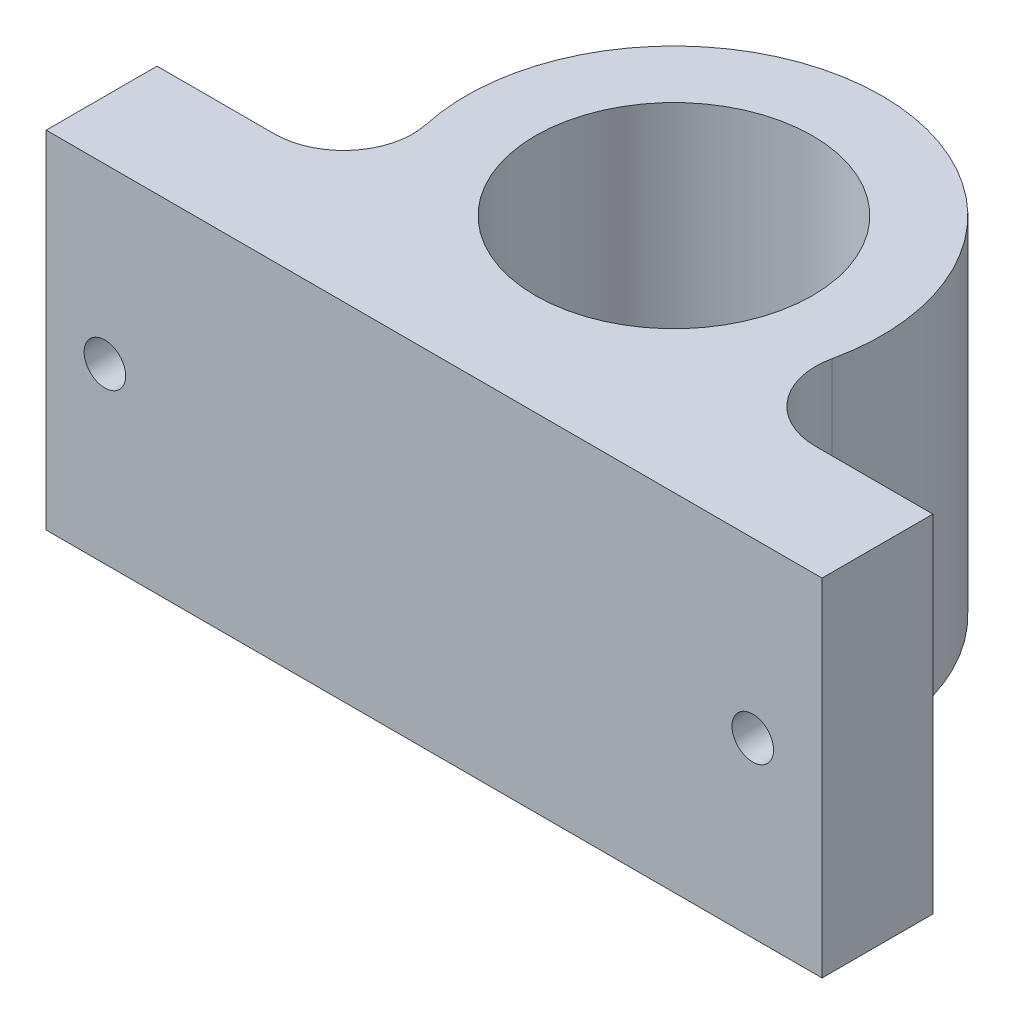
SolidWorks part; units mm, degrees
ref_plane "Front Plane" through (0, 0, 0) normal (0, 0, 1) x (1, 0, 0)
ref_plane "Top Plane" through (0, 0, 0) normal (0, 1, 0) x (1, 0, 0)
ref_plane "Right Plane" through (0, 0, 0) normal (1, 0, 0) x (0, 0, -1)
sketch "Sketch1" plane through (0, 0, 0) normal (0, 1, 0) x (1, 0, 0)
  line L0 (0, 0) -> (-28, 0)
  line L1 (-28, 0) -> (-28, 8)
  line L2 (-28, 8) -> (-11.761, 8)
  line L3 (0, 34.6203) -> (0, 0) construction
  line L7 (0, 0) -> (28, 0)
  line L8 (28, 0) -> (28, 8)
  line L9 (28, 8) -> (11.761, 8)
  circle A2 centre (0, 17.3101) radius 10
  arc A4 (-11.761, 8) -> (11.761, 8) centre (0, 17.3101) cw
  point P3 (-12, 8)
  point P5 (15.3225, 10.5019)
  point P11 (50, 9.9577)
  point P15 (-16.4488, 10)
  dimension "D1" = 20
  dimension "D2" = 15
  dimension "D3" = 28
  dimension "D4" = 8
  dimension "D5" = 28
  dimension "D6" = 8
extrude "Boss-Extrude1" add sketch "Sketch1" along normal blind 25 contours L9 A4 L2 L1 L0 L7 L8 | A2
fillet "Fillet2" radius 5 1 edges at (11.761, 12.5, -8)
fillet "Fillet3" radius 5 1 edges at (-11.761, 12.5, -8)
sketch "Sketch4" plane through (0, 0, -8) normal (0, 0, -1) x (-1, 0, 0)
  line L0 (-28, 25) -> (-28, 0) construction
  line L1 (-23, 25) -> (-23, 0) construction
  line L4 (23.765, 25) -> (23.765, 0) construction
  line L7 (-28, 25) -> (-19.53, 25) construction
  line L8 (-28, 0) -> (-19.53, 0) construction
  line L9 (28, 25) -> (19.53, 25) construction
  line L10 (28, 0) -> (19.53, 0) construction
  point P0 (-23, 12.5)
  point P1 (23.765, 12.5)
  dimension "D1" = 5
hole_wizard "Ø3.0mm Dowel Hole1" positions "3DSketch1" profile "Sketch7" hole size "Ø3.0" standard "ISO"
sketch3d "3DSketch1"
  line L0 (-23.765, 25, -8) -> (-23.765, 0, -8) construction
  point P0 (23, 12.5, -8)
  point P3 (-23.765, 12.5, -8)
  point P7 (-23.765, 12.5, -8)
sketch "Sketch7" plane through (23, 12.5, -8) normal (1, 0, 0) x (0, 1, 0)
  line L0 (0, 0) -> (0, 13.3013)
  line L1 (0, 13.3013) -> (1.5, 12.4)
  line L2 (1.5, 12.4) -> (1.5, 0)
  line L5 (1.5, 0) -> (0, 0)
  line L10 (0, 13.3013) -> (-1.5, 12.4) construction
  line L11 (0, -6.35) -> (0, 107.95) construction
  dimension "Hole Dia." = 3
  dimension "Hole Depth" = 12.4
  dimension "Drill Angle" = 118
